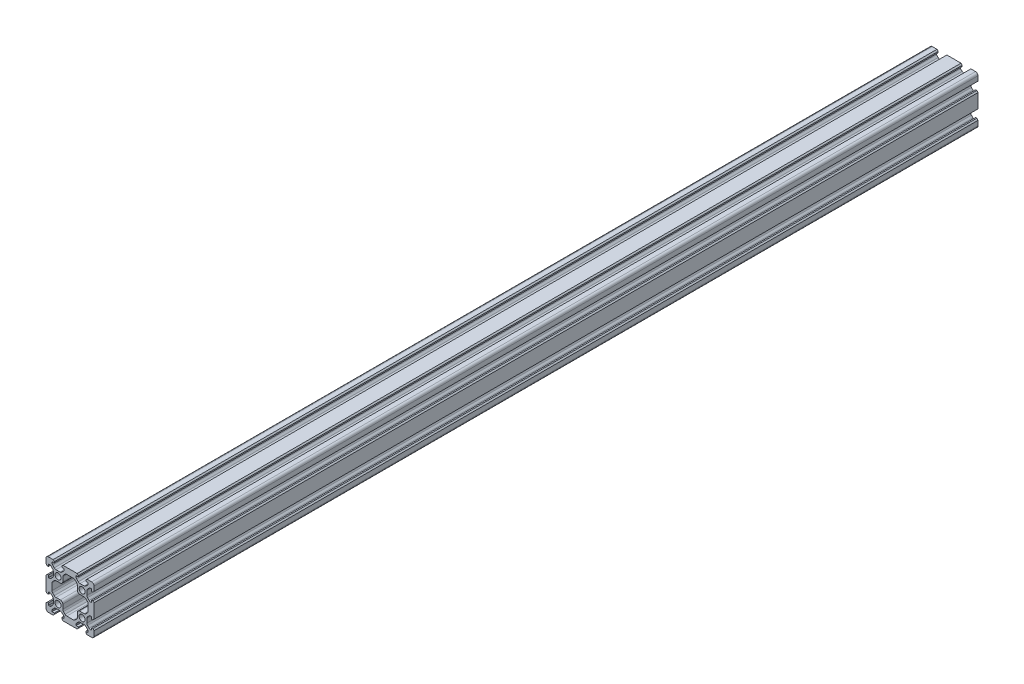
SolidWorks part; units mm, degrees
ref_plane "Front Plane" through (0, 0, 0) normal (0, 0, 1) x (1, 0, 0)
ref_plane "Top Plane" through (0, 0, 0) normal (0, 1, 0) x (1, 0, 0)
ref_plane "Right Plane" through (0, 0, 0) normal (1, 0, 0) x (0, 0, -1)
sketch "Sketch1" plane through (0, 0, 0) normal (0, 0, 1) x (1, 0, 0)
  point P0 (6.9, 0)
  point P1 (0, 6.9)
  point P2 (10, 0)
  point P5 (13.1, 0)
  point P8 (0, 13.1)
  point P9 (-13.1, 0)
  point P21 (10, 0)
  point P22 (10, 0)
  point P23 (6.9, 0)
  point P102 (-6.9, 0)
  line B0 (-4.1716, -14.4142) -> (-5.4621, -13.1236)
  line B1 (-2.7574, -15) -> (2.7574, -15)
  line B2 (-11.7094, -6.0479) -> (-8.0479, -6.0479)
  line B3 (-6.0479, -8.0479) -> (-6.0479, -11.7094)
  line B4 (-13.1236, -5.4621) -> (-14.4142, -4.1716)
  line B5 (-13.1, -19) -> (-14.1, -20)
  line B6 (5.9, -20) -> (-5.9, -20)
  line B7 (-5.9, -20) -> (-6.9, -19)
  line B8 (-14.4142, -15.8284) -> (-13.1236, -14.5379)
  line B9 (-15, -17.2426) -> (-15, -18)
  line B10 (-13.1, -18) -> (-15, -18)
  line B11 (-5, -17.2426) -> (-5, -18)
  line B12 (-5, -18) -> (-6.9, -18)
  line B13 (-6.9, -18) -> (-6.9, -19)
  line B14 (-13.1, -18) -> (-13.1, -19)
  line B15 (-8.2906, -13.9521) -> (-11.7094, -13.9521)
  line B16 (-14.1, -20) -> (-18, -20)
  line B17 (-6.8764, -14.5379) -> (-5.5858, -15.8284)
  line B18 (-19, -6.9) -> (-20, -5.9)
  line B19 (-20, -18) -> (-20, -14.1)
  line B20 (-20, -14.1) -> (-19, -13.1)
  line B21 (-15.8284, -5.5858) -> (-14.5379, -6.8764)
  line B22 (-17.2426, -5) -> (-18, -5)
  line B23 (-18, -6.9) -> (-18, -5)
  line B24 (-17.2426, -15) -> (-18, -15)
  line B25 (-18, -15) -> (-18, -13.1)
  line B26 (-18, -13.1) -> (-19, -13.1)
  line B27 (-18, -6.9) -> (-19, -6.9)
  line B28 (-13.9521, -11.7094) -> (-13.9521, -8.2906)
  line B29 (-14.5379, -13.1236) -> (-15.8284, -14.4142)
  line B30 (-2.7574, 15) -> (2.7574, 15)
  line B31 (-14.4142, 4.1716) -> (-13.1236, 5.4621)
  line B32 (-15, 2.7574) -> (-15, -2.7574)
  line B33 (-6.0479, 11.7094) -> (-6.0479, 8.0479)
  line B34 (-8.0479, 6.0479) -> (-11.7094, 6.0479)
  line B35 (-5.4621, 13.1236) -> (-4.1716, 14.4142)
  line B36 (-19, 13.1) -> (-20, 14.1)
  line B37 (-20, -5.9) -> (-20, 5.9)
  line B38 (-20, 5.9) -> (-19, 6.9)
  line B39 (-15.8284, 14.4142) -> (-14.5379, 13.1236)
  line B40 (-17.2426, 15) -> (-18, 15)
  line B41 (-18, 13.1) -> (-18, 15)
  line B42 (-17.2426, 5) -> (-18, 5)
  line B43 (-18, 5) -> (-18, 6.9)
  line B44 (-18, 6.9) -> (-19, 6.9)
  line B45 (-18, 13.1) -> (-19, 13.1)
  line B46 (-13.9521, 8.2906) -> (-13.9521, 11.7094)
  line B47 (-20, 14.1) -> (-20, 18)
  line B48 (-14.5379, 6.8764) -> (-15.8284, 5.5858)
  line B49 (-6.9, 19) -> (-5.9, 20)
  line B50 (-18, 20) -> (-14.1, 20)
  line B51 (-14.1, 20) -> (-13.1, 19)
  line B52 (-5.5858, 15.8284) -> (-6.8764, 14.5379)
  line B53 (-5, 17.2426) -> (-5, 18)
  line B54 (-6.9, 18) -> (-5, 18)
  line B55 (-15, 17.2426) -> (-15, 18)
  line B56 (-15, 18) -> (-13.1, 18)
  line B57 (-13.1, 18) -> (-13.1, 19)
  line B58 (-6.9, 18) -> (-6.9, 19)
  line B59 (-11.7094, 13.9521) -> (-8.2906, 13.9521)
  line B60 (5.9, 20) -> (-5.9, 20)
  line B61 (-13.1236, 14.5379) -> (-14.4142, 15.8284)
  line B62 (15, 2.7574) -> (15, -2.7574)
  line B63 (4.1716, 14.4142) -> (5.4621, 13.1236)
  line B64 (11.7094, 6.0479) -> (8.0479, 6.0479)
  line B65 (6.0479, 8.0479) -> (6.0479, 11.7094)
  line B66 (13.1236, 5.4621) -> (14.4142, 4.1716)
  line B67 (13.1, 19) -> (14.1, 20)
  line B68 (5.9, 20) -> (6.9, 19)
  line B69 (14.4142, 15.8284) -> (13.1236, 14.5379)
  line B70 (15, 17.2426) -> (15, 18)
  line B71 (13.1, 18) -> (15, 18)
  line B72 (5, 17.2426) -> (5, 18)
  line B73 (5, 18) -> (6.9, 18)
  line B74 (6.9, 18) -> (6.9, 19)
  line B75 (13.1, 18) -> (13.1, 19)
  line B76 (8.2906, 13.9521) -> (11.7094, 13.9521)
  line B77 (14.1, 20) -> (18, 20)
  line B78 (6.8764, 14.5379) -> (5.5858, 15.8284)
  line B79 (19, 6.9) -> (20, 5.9)
  line B80 (20, 18) -> (20, 14.1)
  line B81 (20, 14.1) -> (19, 13.1)
  line B82 (15.8284, 5.5858) -> (14.5379, 6.8764)
  line B83 (17.2426, 5) -> (18, 5)
  line B84 (18, 6.9) -> (18, 5)
  line B85 (17.2426, 15) -> (18, 15)
  line B86 (18, 15) -> (18, 13.1)
  line B87 (18, 13.1) -> (19, 13.1)
  line B88 (18, 6.9) -> (19, 6.9)
  line B89 (13.9521, 11.7094) -> (13.9521, 8.2906)
  line B90 (20, -5.9) -> (20, 5.9)
  line B91 (14.5379, 13.1236) -> (15.8284, 14.4142)
  line B92 (14.4142, -4.1716) -> (13.1236, -5.4621)
  line B93 (6.0479, -11.7094) -> (6.0479, -8.0479)
  line B94 (8.0479, -6.0479) -> (11.7094, -6.0479)
  line B95 (5.4621, -13.1236) -> (4.1716, -14.4142)
  line B96 (19, -13.1) -> (20, -14.1)
  line B97 (20, -5.9) -> (19, -6.9)
  line B98 (15.8284, -14.4142) -> (14.5379, -13.1236)
  line B99 (17.2426, -15) -> (18, -15)
  line B100 (18, -13.1) -> (18, -15)
  line B101 (17.2426, -5) -> (18, -5)
  line B102 (18, -5) -> (18, -6.9)
  line B103 (18, -6.9) -> (19, -6.9)
  line B104 (18, -13.1) -> (19, -13.1)
  line B105 (13.9521, -8.2906) -> (13.9521, -11.7094)
  line B106 (20, -14.1) -> (20, -18)
  line B107 (14.5379, -6.8764) -> (15.8284, -5.5858)
  line B108 (6.9, -19) -> (5.9, -20)
  line B109 (18, -20) -> (14.1, -20)
  line B110 (14.1, -20) -> (13.1, -19)
  line B111 (5.5858, -15.8284) -> (6.8764, -14.5379)
  line B112 (5, -17.2426) -> (5, -18)
  line B113 (6.9, -18) -> (5, -18)
  line B114 (15, -17.2426) -> (15, -18)
  line B115 (15, -18) -> (13.1, -18)
  line B116 (13.1, -18) -> (13.1, -19)
  line B117 (6.9, -18) -> (6.9, -19)
  line B118 (11.7094, -13.9521) -> (8.2906, -13.9521)
  line B119 (13.1236, -14.5379) -> (14.4142, -15.8284)
  circle B120 centre (-10, -10) radius 2.5
  arc B121 (-14.5379, -6.8764) -> (-13.9521, -8.2906) centre (-15.9521, -8.2906) cw
  arc B122 (-15.8284, -5.5858) -> (-17.2426, -5) centre (-17.2426, -7) ccw
  arc B123 (-15, -2.7574) -> (-14.4142, -4.1716) centre (-13, -2.7574) ccw
  arc B124 (6.0479, 8.0479) -> (8.0479, 6.0479) centre (8.0479, 8.0479) ccw
  arc B125 (8.0479, -6.0479) -> (6.0479, -8.0479) centre (8.0479, -8.0479) ccw
  arc B126 (-4.1716, -14.4142) -> (-2.7574, -15) centre (-2.7574, -13) ccw
  arc B127 (-5, -17.2426) -> (-5.5858, -15.8284) centre (-7, -17.2426) ccw
  arc B128 (-14.4142, -15.8284) -> (-15, -17.2426) centre (-13, -17.2426) ccw
  arc B129 (-17.2426, -15) -> (-15.8284, -14.4142) centre (-17.2426, -13) ccw
  arc B130 (-13.9521, -11.7094) -> (-14.5379, -13.1236) centre (-15.9521, -11.7094) cw
  arc B131 (-13.1236, -14.5379) -> (-11.7094, -13.9521) centre (-11.7094, -15.9521) cw
  arc B132 (-8.2906, -13.9521) -> (-6.8764, -14.5379) centre (-8.2906, -15.9521) cw
  arc B133 (-5.4621, -13.1236) -> (-6.0479, -11.7094) centre (-4.0479, -11.7094) cw
  arc B134 (-6.0479, -8.0479) -> (-8.0479, -6.0479) centre (-8.0479, -8.0479) ccw
  arc B135 (-6.0479, 8.0479) -> (-8.0479, 6.0479) centre (-8.0479, 8.0479) cw
  arc B136 (-11.7094, -6.0479) -> (-13.1236, -5.4621) centre (-11.7094, -4.0479) cw
  arc B137 (-18, -20) -> (-20, -18) centre (-18, -18) cw
  circle B138 centre (-10, 10) radius 2.5
  arc B139 (-6.8764, 14.5379) -> (-8.2906, 13.9521) centre (-8.2906, 15.9521) cw
  arc B140 (-5.5858, 15.8284) -> (-5, 17.2426) centre (-7, 17.2426) ccw
  arc B141 (-2.7574, 15) -> (-4.1716, 14.4142) centre (-2.7574, 13) ccw
  arc B142 (-14.4142, 4.1716) -> (-15, 2.7574) centre (-13, 2.7574) ccw
  arc B143 (-17.2426, 5) -> (-15.8284, 5.5858) centre (-17.2426, 7) ccw
  arc B144 (-15.8284, 14.4142) -> (-17.2426, 15) centre (-17.2426, 13) ccw
  arc B145 (-15, 17.2426) -> (-14.4142, 15.8284) centre (-13, 17.2426) ccw
  arc B146 (-11.7094, 13.9521) -> (-13.1236, 14.5379) centre (-11.7094, 15.9521) cw
  arc B147 (-14.5379, 13.1236) -> (-13.9521, 11.7094) centre (-15.9521, 11.7094) cw
  arc B148 (-13.9521, 8.2906) -> (-14.5379, 6.8764) centre (-15.9521, 8.2906) cw
  arc B149 (-13.1236, 5.4621) -> (-11.7094, 6.0479) centre (-11.7094, 4.0479) cw
  arc B150 (-6.0479, 11.7094) -> (-5.4621, 13.1236) centre (-4.0479, 11.7094) cw
  arc B151 (-20, 18) -> (-18, 20) centre (-18, 18) cw
  circle B152 centre (10, 10) radius 2.5
  arc B153 (14.5379, 6.8764) -> (13.9521, 8.2906) centre (15.9521, 8.2906) cw
  arc B154 (15.8284, 5.5858) -> (17.2426, 5) centre (17.2426, 7) ccw
  arc B155 (15, 2.7574) -> (14.4142, 4.1716) centre (13, 2.7574) ccw
  arc B156 (4.1716, 14.4142) -> (2.7574, 15) centre (2.7574, 13) ccw
  arc B157 (5, 17.2426) -> (5.5858, 15.8284) centre (7, 17.2426) ccw
  arc B158 (14.4142, 15.8284) -> (15, 17.2426) centre (13, 17.2426) ccw
  arc B159 (17.2426, 15) -> (15.8284, 14.4142) centre (17.2426, 13) ccw
  arc B160 (13.9521, 11.7094) -> (14.5379, 13.1236) centre (15.9521, 11.7094) cw
  arc B161 (13.1236, 14.5379) -> (11.7094, 13.9521) centre (11.7094, 15.9521) cw
  arc B162 (8.2906, 13.9521) -> (6.8764, 14.5379) centre (8.2906, 15.9521) cw
  arc B163 (5.4621, 13.1236) -> (6.0479, 11.7094) centre (4.0479, 11.7094) cw
  arc B164 (11.7094, 6.0479) -> (13.1236, 5.4621) centre (11.7094, 4.0479) cw
  arc B165 (18, 20) -> (20, 18) centre (18, 18) cw
  circle B166 centre (10, -10) radius 2.5
  arc B167 (6.8764, -14.5379) -> (8.2906, -13.9521) centre (8.2906, -15.9521) cw
  arc B168 (5.5858, -15.8284) -> (5, -17.2426) centre (7, -17.2426) ccw
  arc B169 (2.7574, -15) -> (4.1716, -14.4142) centre (2.7574, -13) ccw
  arc B170 (14.4142, -4.1716) -> (15, -2.7574) centre (13, -2.7574) ccw
  arc B171 (17.2426, -5) -> (15.8284, -5.5858) centre (17.2426, -7) ccw
  arc B172 (15.8284, -14.4142) -> (17.2426, -15) centre (17.2426, -13) ccw
  arc B173 (15, -17.2426) -> (14.4142, -15.8284) centre (13, -17.2426) ccw
  arc B174 (11.7094, -13.9521) -> (13.1236, -14.5379) centre (11.7094, -15.9521) cw
  arc B175 (14.5379, -13.1236) -> (13.9521, -11.7094) centre (15.9521, -11.7094) cw
  arc B176 (13.9521, -8.2906) -> (14.5379, -6.8764) centre (15.9521, -8.2906) cw
  arc B177 (13.1236, -5.4621) -> (11.7094, -6.0479) centre (11.7094, -4.0479) cw
  arc B178 (6.0479, -11.7094) -> (5.4621, -13.1236) centre (4.0479, -11.7094) cw
  arc B179 (20, -18) -> (18, -20) centre (18, -18) cw
sketch_block_instance "4040-1"
sketch_block "4040" parameters "D1"=2, "D2"=2
extrude "Boss-Extrude1" add sketch "Sketch1" along normal blind 735
